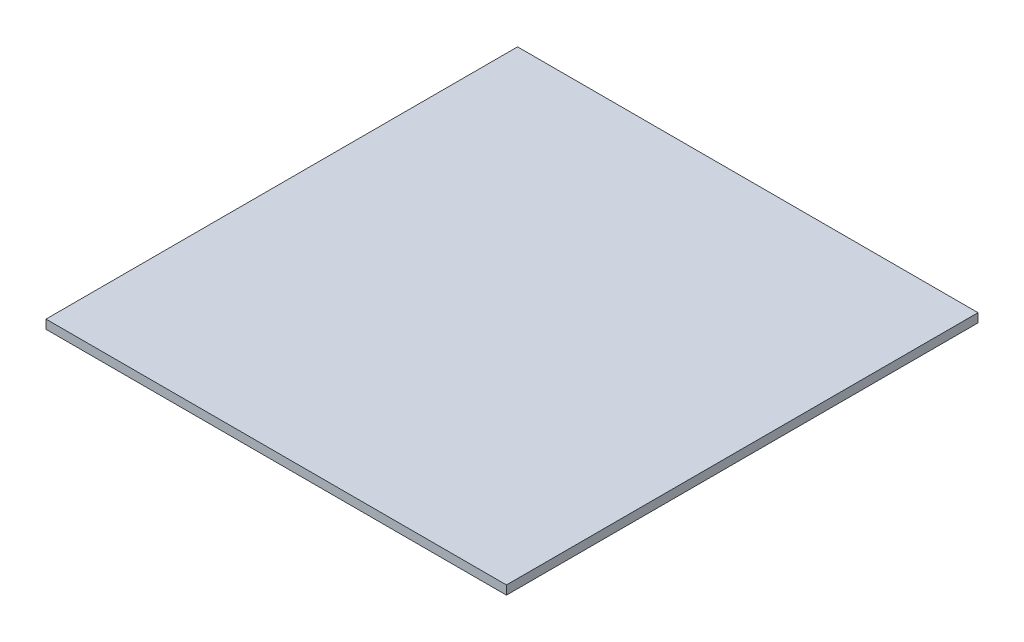
SolidWorks part; units mm, degrees
ref_plane "Front Plane" through (0, 0, 0) normal (0, 0, 1) x (1, 0, 0)
ref_plane "Top Plane" through (0, 0, 0) normal (0, 1, 0) x (1, 0, 0)
ref_plane "Right Plane" through (0, 0, 0) normal (1, 0, 0) x (0, 0, -1)
sketch "Sketch1" plane through (0, 0, 0) normal (0, 1, 0) x (1, 0, 0)
  line L1 (-41.5, -42.5) -> (41.5, -42.5)
  line L2 (-41.5, -42.5) -> (-41.5, 42.5)
  line L3 (-41.5, 42.5) -> (41.5, 42.5)
  line L4 (41.5, -42.5) -> (41.5, 42.5)
  line L5 (-41.5, -42.5) -> (41.5, 42.5) construction
  line L6 (-41.5, 42.5) -> (41.5, -42.5) construction
  point P0 (0, 0)
  dimension "D1" = 83
  dimension "D2" = 85
extrude "Boss-Extrude1" add sketch "Sketch1" along normal blind 1.6
